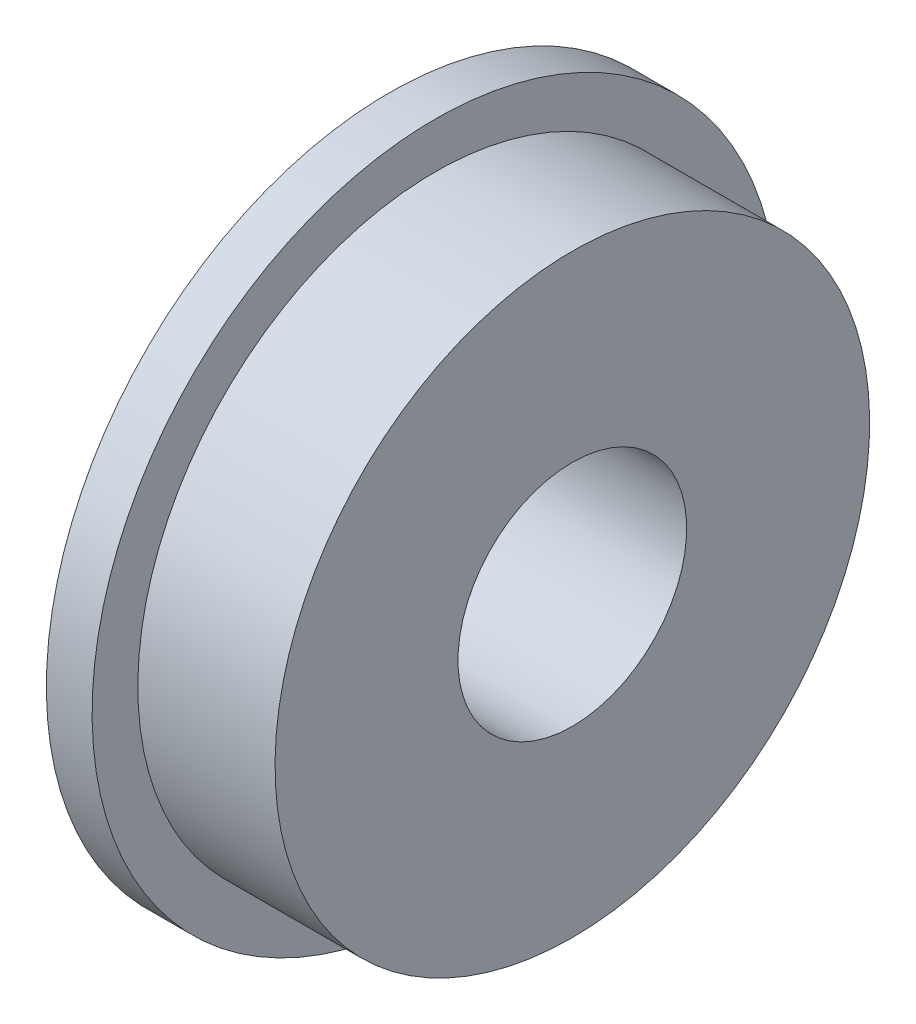
SolidWorks part; units mm, degrees
ref_plane "前视基准面" through (0, 0, 0) normal (0, 0, 1) x (1, 0, 0)
ref_plane "上视基准面" through (0, 0, 0) normal (0, 1, 0) x (1, 0, 0)
ref_plane "右视基准面" through (0, 0, 0) normal (1, 0, 0) x (0, 0, -1)
sketch "Model" plane through (0, 0, 0) normal (0, 0, 1) x (1, 0, 0)
  line L0 (0.1442, 3.5914) -> (8.1442, 3.5914) construction
  line L1 (4.1442, -0.4086) -> (4.1442, 7.5914) construction
  line L2 (22.2863, 3.5914) -> (14.2863, 3.5914) construction
  line L3 (18.2863, -0.4086) -> (18.2863, 7.5914) construction
  line L4 (-21.069, -17.6218) -> (-13.069, -17.6218) construction
  line L5 (-17.069, -21.6218) -> (-17.069, -13.6218) construction
  line L6 (43.4995, -17.6218) -> (35.4995, -17.6218) construction
  line L7 (39.4995, -21.6218) -> (39.4995, -13.6218) construction
  line L8 (-35.1609, 21.2575) -> (-26.1609, 21.2575)
  line L9 (-26.1609, 23.2575) -> (-22.3679, 23.2575)
  line L10 (-22.6609, 21.2575) -> (-16.3609, 69.2575)
  line L11 (-22.6609, 21.2575) -> (-38.6609, 21.2575)
  line L12 (-35.1609, 23.2575) -> (-38.9539, 23.2575)
  line L13 (-38.6609, 21.2575) -> (-44.9609, 69.2575)
  line L14 (-24.1609, 96.2575) -> (-16.3609, 73.2575)
  line L15 (-37.1609, 96.2575) -> (-24.1609, 96.2575)
  line L16 (-37.1609, 96.2575) -> (-44.9609, 73.2575)
  line L17 (-16.3609, 69.2575) -> (-16.3609, 73.2575)
  line L18 (-44.9609, 69.2575) -> (-44.9609, 73.2575)
  line L19 (-26.1609, 21.2575) -> (-26.1609, 23.2575)
  line L20 (-35.1609, 21.2575) -> (-35.1609, 23.2575)
  line L21 (29.9233, 62.9292) -> (29.9233, 69.9371)
  line L22 (29.9233, 62.9292) -> (29.9233, 35.9571)
  line L23 (1.3233, 62.9292) -> (1.3233, 35.9571)
  line L24 (1.3233, 69.9371) -> (29.9233, 69.9371)
  line L25 (1.3233, 62.9292) -> (1.3233, 69.9371)
  line L26 (62.8459, 91.9277) -> (70.6459, 68.9277)
  line L27 (49.8459, 91.9277) -> (42.0459, 68.9277)
  line L28 (49.8459, 91.9277) -> (62.8459, 91.9277)
  line L29 (64.3459, 16.9277) -> (70.6459, 64.9277)
  line L30 (48.3459, 16.9277) -> (42.0459, 64.9277)
  line L31 (64.3459, 16.9277) -> (48.3459, 16.9277)
  line L32 (70.6459, 64.9277) -> (70.6459, 68.9277)
  line L33 (42.0459, 64.9277) -> (42.0459, 68.9277)
  line L34 (42.0459, 68.9277) -> (70.6459, 68.9277)
  line L35 (98.2506, 52.8636) -> (103.9075, 58.5204)
  line L36 (94.3615, 56.7527) -> (98.2506, 52.8636)
  line L37 (84.1085, 67.0057) -> (89.7653, 72.6626)
  line L38 (84.1085, 67.0057) -> (87.9976, 63.1166)
  line L39 (90.4724, 65.5915) -> (96.8364, 59.2275)
  line L40 (89.7653, 72.6626) -> (103.9075, 58.5204)
  line L41 (87.6457, 43.7153) -> (91.5348, 47.6044)
  line L42 (81.2817, 50.0793) -> (87.6457, 43.7153)
  line L43 (85.1708, 53.9684) -> (91.5348, 47.6044)
  line L44 (81.2817, 50.0793) -> (85.1708, 53.9684)
  line L45 (94.3615, 56.7527) -> (96.8364, 59.2275)
  line L46 (87.9976, 63.1166) -> (90.4724, 65.5915)
  line L47 (105.6938, 43.5) -> (114.4938, 43.5)
  line L48 (114.4938, 43.5) -> (114.4938, 37)
  line L49 (103.6938, 37) -> (105.6938, 37)
  line L50 (114.4938, 37) -> (116.4938, 37)
  line L51 (116.4938, 36) -> (122.0938, 36)
  line L52 (116.4938, 37) -> (116.4938, 36)
  line L53 (103.6938, 37) -> (103.6938, 36)
  line L54 (98.0938, 36) -> (103.6938, 36)
  line L55 (85.0938, 35.5) -> (98.0938, 35.5)
  line L56 (122.0938, 36) -> (122.0938, 35.5)
  line L57 (122.0938, 35.5) -> (126.0938, 35.5)
  line L58 (105.6938, 37) -> (105.6938, 43.5)
  line L59 (98.0938, 36) -> (98.0938, 35.5)
  line L60 (85.0938, 33) -> (126.0938, 33)
  line L61 (85.0938, 35.5) -> (85.0938, 33)
  line L62 (126.0938, 35.5) -> (126.0938, 33)
  line L63 (100.4858, 19.3209) -> (103.4858, 19.3209)
  line L64 (99.4858, 18.3209) -> (100.4858, 18.3209)
  line L65 (100.4858, 19.3209) -> (100.4858, 18.3209)
  line L66 (99.4858, 22.8209) -> (99.4858, 18.3209)
  line L67 (99.4858, 23.3209) -> (103.4858, 23.3209)
  line L68 (99.4858, 23.3209) -> (99.4858, 22.8209)
  line L69 (103.4858, 23.3209) -> (103.4858, 19.3209)
  line L70 (69.3289, 25.8209) -> (110.0953, 25.8209) construction
  line L71 (51.5203, -32.4711) -> (50.1061, -33.8853)
  line L72 (14.6416, 10.0645) -> (68.4909, -43.7848)
  line L73 (65.6624, -46.6132) -> (51.5203, -32.4711)
  line L74 (65.6624, -46.6132) -> (68.4909, -43.7848)
  line L75 (50.1061, -33.8853) -> (49.035, -32.8142)
  line L76 (11.2152, -31.9355) -> (46.9137, -31.9355)
  line L77 (38.2152, -22.9772) -> (38.2152, -31.9355)
  line L78 (42.3279, -17.6218) -> (39.0939, -20.8558)
  line L79 (4.2741, 1.0645) -> (18.1564, 1.0645)
  line L80 (-25.8848, -23.9355) -> (-15.6848, -23.9355) construction
  line L81 (-20.7848, -29.0355) -> (-20.7848, -18.8355) construction
  line L82 (6.1152, 6.0645) -> (16.3152, 6.0645) construction
  line L83 (11.2152, 0.9645) -> (11.2152, 11.1645) construction
  line L84 (11.2152, -0.5802) -> (11.2152, 13.4198) construction
  line L85 (7.7888, 10.0645) -> (14.6416, 10.0645)
  line L86 (4.1442, 6.4198) -> (7.6208, 2.9431)
  line L87 (9.7421, 2.0645) -> (12.6883, 2.0645)
  line L88 (18.2863, 6.4198) -> (14.8096, 2.9431)
  line L89 (2.1528, 0.1858) -> (-12.9061, -14.8731)
  line L90 (-13.7848, -16.9944) -> (-13.7848, -25.9355)
  line L91 (36.2152, -16.9944) -> (36.2152, -25.9355)
  line L92 (53.6416, -28.9355) -> (33.2152, -28.9355) construction
  line L93 (-10.7848, -28.9355) -> (33.2152, -28.9355)
  line L94 (20.2777, 0.1858) -> (35.3366, -14.8731)
  line L95 (-19.8975, -17.6218) -> (-16.6635, -20.8558)
  line L96 (-15.7848, -22.9772) -> (-15.7848, -31.9355)
  line L97 (-24.4833, -31.9355) -> (11.2152, -31.9355)
  line L98 (3.2152, -27.0355) -> (3.2152, -31.9355)
  line L99 (19.2152, -27.0355) -> (19.2152, -31.9355)
  line L100 (19.2152, -27.0355) -> (3.2152, -27.0355)
  line L101 (7.7888, 10.0645) -> (-46.0604, -43.7848)
  line L102 (-43.232, -46.6132) -> (-46.0604, -43.7848)
  line L103 (-43.232, -46.6132) -> (-29.0899, -32.4711)
  line L104 (-29.0899, -32.4711) -> (-27.6756, -33.8853)
  line L105 (-27.6756, -33.8853) -> (-26.6046, -32.8142)
  line L106 (25.2152, -30.4355) -> (17.2152, -30.4355) construction
  line L107 (21.2152, -34.4355) -> (21.2152, -26.4355) construction
  line L108 (40.2152, -30.4355) -> (32.2152, -30.4355) construction
  line L109 (36.2152, -34.4355) -> (36.2152, -26.4355) construction
  line L110 (-2.7848, -30.4355) -> (5.2152, -30.4355) construction
  line L111 (1.2152, -34.4355) -> (1.2152, -26.4355) construction
  line L112 (-17.7848, -30.4355) -> (-9.7848, -30.4355) construction
  line L113 (-13.7848, -34.4355) -> (-13.7848, -26.4355) construction
  circle A0 centre (4.1442, 3.5914) radius 0.7835
  arc A1 (4.1442, 2.5914) -> (3.1593, 3.4177) centre (4.1442, 3.5914) ccw
  circle A2 centre (18.2863, 3.5914) radius 0.7835
  arc A3 (19.2711, 3.4177) -> (18.2863, 2.5914) centre (18.2863, 3.5914) ccw
  circle A4 centre (-17.069, -17.6218) radius 0.7835
  arc A5 (-17.069, -18.6218) -> (-18.0539, -17.7955) centre (-17.069, -17.6218) ccw
  circle A6 centre (39.4995, -17.6218) radius 0.7835
  arc A7 (40.4843, -17.7955) -> (39.4995, -18.6218) centre (39.4995, -17.6218) ccw
  arc A8 (1.3233, 35.9571) -> (29.9233, 35.9571) centre (15.6233, 41.9371) ccw
  circle A9 centre (56.3459, 36.9277) radius 6.5
  arc A10 (49.035, -32.8142) -> (46.9137, -31.9355) centre (46.9137, -34.9355) ccw
  arc A11 (39.0939, -20.8558) -> (38.2152, -22.9772) centre (41.2152, -22.9772) ccw
  arc A12 (20.2777, 0.1858) -> (18.1564, 1.0645) centre (18.1564, -1.9355) ccw
  arc A13 (4.2741, 1.0645) -> (2.1528, 0.1858) centre (4.2741, -1.9355) ccw
  circle A14 centre (-20.7848, -23.9355) radius 2.1
  circle A15 centre (43.2152, -23.9355) radius 2.1
  circle A16 centre (11.2152, 6.0645) radius 2.1
  arc A17 (7.6208, 2.9431) -> (9.7421, 2.0645) centre (9.7421, 5.0645) ccw
  arc A18 (12.6883, 2.0645) -> (14.8096, 2.9431) centre (12.6883, 5.0645) ccw
  arc A19 (-12.9061, -14.8731) -> (-13.7848, -16.9944) centre (-10.7848, -16.9944) ccw
  arc A20 (-13.7848, -25.9355) -> (-10.7848, -28.9355) centre (-10.7848, -25.9355) ccw
  arc A21 (36.2152, -16.9944) -> (35.3366, -14.8731) centre (33.2152, -16.9944) ccw
  arc A22 (33.2152, -28.9355) -> (36.2152, -25.9355) centre (33.2152, -25.9355) ccw
  arc A23 (-24.4833, -31.9355) -> (-26.6046, -32.8142) centre (-24.4833, -34.9355) ccw
  arc A24 (-15.7848, -22.9772) -> (-16.6635, -20.8558) centre (-18.7848, -22.9772) ccw
revolve "旋转1" add sketch "Model" angle 360 about L70
